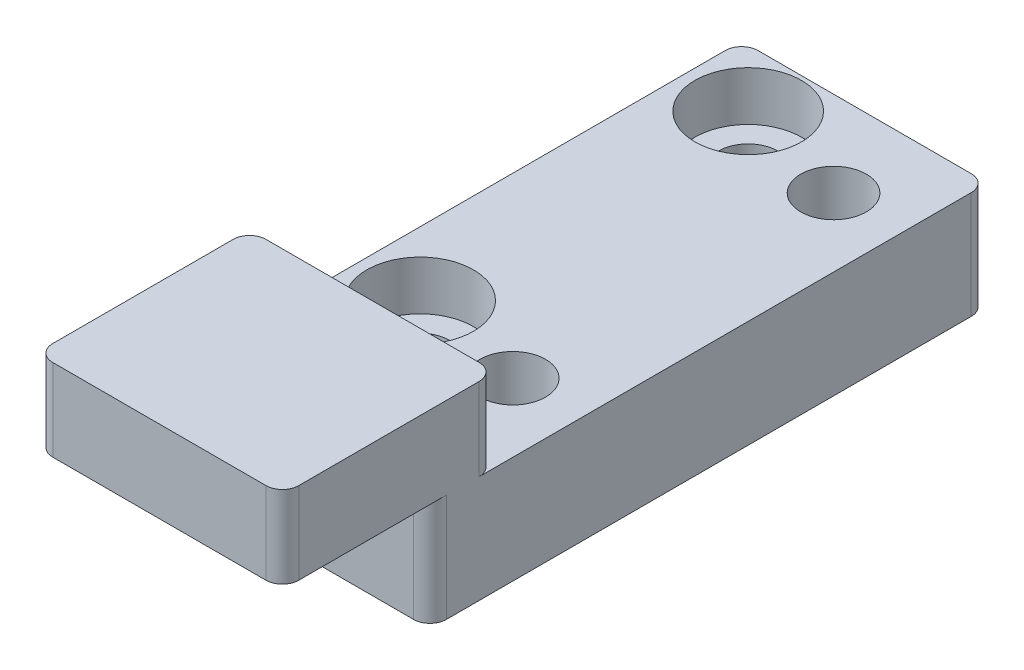
SolidWorks part; units mm, degrees
material "ABS"
ref_plane "Front Plane" through (0, 0, 0) normal (0, 0, 1) x (1, 0, 0)
ref_plane "Top Plane" through (0, 0, 0) normal (0, 1, 0) x (1, 0, 0)
ref_plane "Right Plane" through (0, 0, 0) normal (1, 0, 0) x (0, 0, -1)
sketch "Sketch1" plane through (0, 0, 0) normal (0, 0, 1) x (1, 0, 0)
  line L1 (0, 0) -> (15, 0)
  line L2 (0, 0) -> (0, 6.539)
  line L3 (0, 6.539) -> (15, 6.539)
  line L4 (15, 0) -> (15, 6.539)
  dimension "D1" = 15
  dimension "D2" = 6.539
extrude "Boss-Extrude1" add sketch "Sketch1" along normal blind 30
hole_wizard "CBORE for M3 SHCS1" positions "Sketch2" profile "Sketch3" counterbore size "M3" standard "ANSI Metric" end condition through all
sketch "Sketch2" plane through (0, 6.539, 0) normal (0, 1, 0) x (1, 0, 0)
  point P0 (3.9, -3.5)
  point P3 (3.9, -23.5)
sketch "Sketch3" plane through (3.9, 6.539, 3.5) normal (1, 0, 0) x (0, 0, 1)
  line L0 (0, 0) -> (0, 6.539)
  line L1 (0, 6.539) -> (1.8, 6.539)
  line L3 (1.8, 6.539) -> (1.8, 3)
  line L4 (1.8, 3) -> (3.25, 3)
  line L5 (3.25, 3) -> (3.25, 0)
  line L7 (3.25, 0) -> (0, 0)
  line L11 (0, -6.35) -> (0, 107.95) construction
  dimension "Thru Hole Dia." = 3.6
  dimension "Thru Hole Depth" = 6.539
  dimension "C'Bore Dia." = 6.5
  dimension "C'Bore Depth" = 3
hole_wizard "CBORE for #6 Socket Head Cap Screw1" positions "Sketch4" profile "Sketch5" counterbore size "#6" standard "ANSI Inch" end condition up to next
sketch "Sketch4" plane through (0, 0, 0) normal (0, -1, 0) x (-1, 0, 0)
  point P0 (-10.825, -24.779)
  point P3 (-10.825, -5.221)
sketch "Sketch5" plane through (10.825, 0, 24.779) normal (1, 0, 0) x (0, 0, -1)
  line L0 (0, 0) -> (0, 6.539)
  line L1 (0, 6.539) -> (1.9987, 6.539)
  line L3 (1.9987, 6.539) -> (1.9987, 3.5052)
  line L4 (1.9987, 3.5052) -> (3.5725, 3.5052)
  line L5 (3.5725, 3.5052) -> (3.5725, 0)
  line L7 (3.5725, 0) -> (0, 0)
  line L11 (0, -6.35) -> (0, 107.95) construction
  dimension "Thru Hole Dia." = 3.9973
  dimension "Thru Hole Depth" = 6.539
  dimension "C'Bore Dia." = 7.145
  dimension "C'Bore Depth" = 3.5052
sketch "Sketch6" plane through (15, 0, 0) normal (1, 0, 0) x (0, 0, -1)
  line L0 (-30, 0) -> (-34, 0)
  line L1 (-30, 0) -> (0, 0) construction
  line L2 (-30, 0) -> (-30, 6.539) construction
  line L3 (-34, 0) -> (-34, 6.569)
  line L4 (-34, 6.569) -> (-43, 6.569)
  line L5 (-43, 6.569) -> (-43, 11.569)
  line L6 (-43, 11.569) -> (-30, 11.569)
  line L7 (-30, 11.569) -> (-30, 0)
  dimension "D1" = 4
  dimension "D2" = 6.569
  dimension "D3" = 5
  dimension "D4" = 13
extrude "Boss-Extrude2" add sketch "Sketch6" against normal up to surface (15 mm away) up to face at (0, 3.2695, 15)
fillet "Fillet1" radius 1 8 edges at (15, 3.2695, 0) (0, 3.2695, 0) (15, 9.054, 30) (0, 9.054, 30) (0, 3.2845, 34) (15, 3.2845, 34) (0, 9.069, 43) (15, 9.069, 43)
